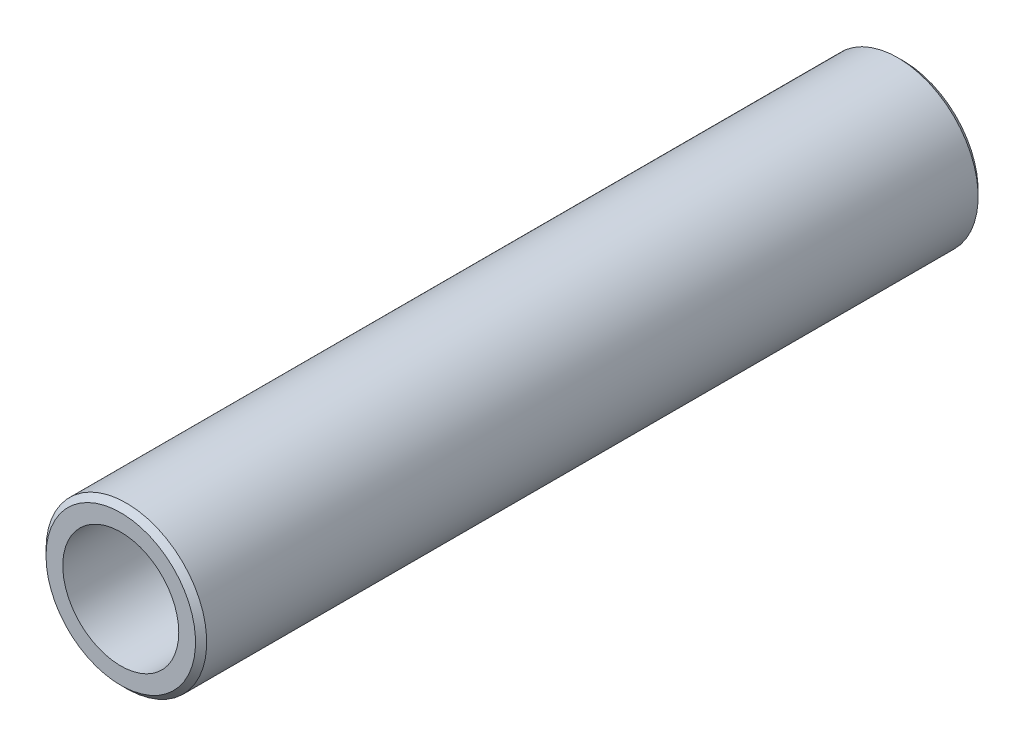
SolidWorks part; units mm, degrees
ref_plane "Alzado" through (0, 0, 0) normal (0, 0, 1) x (1, 0, 0)
ref_plane "Planta" through (0, 0, 0) normal (0, 1, 0) x (1, 0, 0)
ref_plane "Vista lateral" through (0, 0, 0) normal (1, 0, 0) x (0, 0, -1)
ref_plane "Plano1" through (0, 0, 0) normal (0, 0, -1) x (-1, 0, 0)
sketch "Croquis1" plane through (0, 0, 0) normal (0, 0, -1) x (-1, 0, 0)
  circle A0 centre (-5.8, 5.8) radius 5.75
  dimension "D1" = 11.5
extrude "Saliente-Extruir1" add sketch "Croquis1" against normal blind 56
sketch "Croquis2" plane through (0, 0, 56) normal (0, 0, 1) x (1, 0, 0)
  circle A0 centre (5.8, 5.8) radius 4.15
  dimension "D1" = 8.3
extrude "Cortar-Extruir1" cut sketch "Croquis2" against normal through all
chamfer "Chaflán1" distance 0.4 angle 45 1 edges at (0.05, 5.8, 0)
chamfer "Chaflán2" distance 0.4 angle 45 1 edges at (0.05, 5.8, 56)
